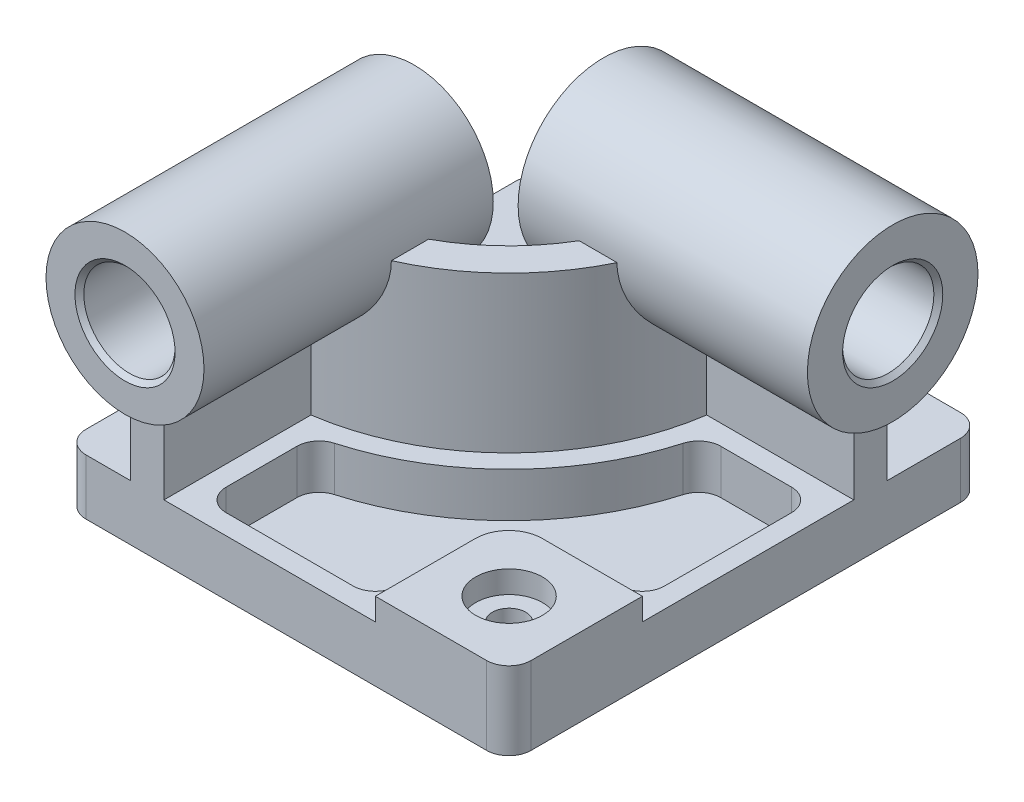
SolidWorks part; units mm, degrees
material "Acier allié"
ref_plane "Plan de face" through (0, 0, 0) normal (0, 0, 1) x (1, 0, 0)
ref_plane "Plan de dessus" through (0, 0, 0) normal (0, 1, 0) x (1, 0, 0)
ref_plane "Plan de droite" through (0, 0, 0) normal (1, 0, 0) x (0, 0, -1)
sketch "Esquisse1" plane through (0, 0, 0) normal (0, 1, 0) x (1, 0, 0)
  line L1 (-100, 106.5) -> (100, 106.5)
  line L2 (-100, 106.5) -> (-100, -106.5)
  line L3 (-100, -106.5) -> (100, -106.5)
  line L4 (100, 106.5) -> (100, -106.5)
  line L5 (-100, 106.5) -> (100, -106.5) construction
  line L6 (-100, -106.5) -> (100, 106.5) construction
  point P0 (0, 0)
  dimension "D1" = 213
  dimension "D2" = 200
extrude "Boss.-Extru.1" add sketch "Esquisse1" along normal blind 25
sketch "Esquisse2" plane through (0, 25, 0) normal (0, 1, 0) x (1, 0, 0)
  line L1 (40, -46.5) -> (100, -46.5)
  line L2 (40, -46.5) -> (40, -106.5)
  line L3 (40, -106.5) -> (100, -106.5)
  line L4 (100, -46.5) -> (100, -106.5)
  line L5 (40, -46.5) -> (100, -106.5) construction
  line L6 (40, -106.5) -> (100, -46.5) construction
  point P0 (70, -76.5)
  point P5 (0, 0)
  dimension "D1" = 60
  dimension "D2" = 60
extrude "Boss.-Extru.2" add sketch "Esquisse2" along normal blind 10
fillet "Congé1" radius 10 4 edges at (-100, 12.5, 106.5) (-100, 12.5, -106.5) (100, 12.5, -106.5) (100, 17.5, 106.5)
fillet "Congé2" radius 15 1 edges at (40, 30, 46.5)
sketch "Esquisse3" plane through (0, 35, 0) normal (0, 1, 0) x (1, 0, 0)
  line L0 (100, -106.3926) -> (100, -76.3926) construction
  line L1 (100, -96.5) -> (100, -46.5) construction
  line L2 (100, -76.3926) -> (70, -76.3926) construction
  dimension "D1" = 30
  dimension "D2" = 30
hole_wizard "Chambrage pour vis à tête hexagonale M86" positions "Esquisse8" profile "Esquisse7" counterbore size "M8" standard "Ansi Metric" end condition through all
sketch "Esquisse8" plane through (0, 35, 0) normal (0, 1, 0) x (1, 0, 0)
  point P0 (70, -76.3926)
  point P2 (0, 0)
sketch "Esquisse7" plane through (70, 35, 76.3926) normal (1, 0, 0) x (0, 0, 1)
  line L0 (0, 0) -> (0, 35)
  line L1 (0, 35) -> (7.5, 35)
  line L3 (7.5, 35) -> (7.5, 10)
  line L4 (7.5, 10) -> (15, 10)
  line L5 (15, 10) -> (15, 0)
  line L7 (15, 0) -> (0, 0)
  line L11 (0, -6.35) -> (0, 107.95) construction
  dimension "Diamètre du perçage jusqu'au prochain" = 15
  dimension "Profondeur du perçage jusqu'au prochain" = 35
  dimension "Diamètre du chambrage" = 30
  dimension "Profondeur du chambrage" = 10
sketch "Esquisse9" plane through (0, 25, 0) normal (0, 1, 0) x (1, 0, 0)
  line L0 (-70, -106.5) -> (-70, -26.5)
  line L1 (-90, -106.5) -> (40, -106.5) construction
  line L2 (100, 63.5) -> (20, 63.5)
  line L3 (100, -46.5) -> (100, 96.5) construction
  line L4 (100, 48.5) -> (33.923, 48.5)
  line L5 (-55, -106.5) -> (-55, -40.423)
  line L6 (100, 63.5) -> (100, 48.5)
  line L7 (-55, -106.5) -> (-70, -106.5)
  arc A0 (20, 63.5) -> (-70, -26.5) centre (-70, 63.5) cw
  arc A1 (33.923, 48.5) -> (-55, -40.423) centre (-70, 63.5) cw
  dimension "D1" = 80
  dimension "D2" = 80
  dimension "D3" = 170
  dimension "D4" = 170
  dimension "D5" = 15
extrude "Boss.-Extru.3" add sketch "Esquisse9" along normal blind 70
sketch "Esquisse10" plane through (0, 25, 0) normal (0, 1, 0) x (1, 0, 0)
  line L12 (-46, -47.9451) -> (-46, -97.5)
  line L13 (-46, -97.5) -> (31, -97.5)
  line L14 (31, -97.5) -> (31, -61.5)
  line L15 (55, -37.5) -> (91, -37.5)
  line L16 (91, -37.5) -> (91, 39.5)
  line L17 (91, 39.5) -> (41.4451, 39.5)
  line L18 (-46, -55.7476) -> (-46, -87.5)
  line L19 (-36, -97.5) -> (21, -97.5)
  line L20 (31, -87.5) -> (31, -61.5)
  line L21 (55, -37.5) -> (81, -37.5)
  line L22 (91, -27.5) -> (91, 29.5)
  line L23 (81, 39.5) -> (49.2476, 39.5)
  arc A2 (81, -37.5) -> (91, -27.5) centre (81, -27.5) ccw
  arc A3 (91, 29.5) -> (81, 39.5) centre (81, 29.5) ccw
  arc A4 (-46, -47.9451) -> (41.4451, 39.5) centre (-70, 63.5) ccw
  arc A5 (55, -37.5) -> (31, -61.5) centre (55, -61.5) ccw
  arc A6 (-38.7419, -46.1309) -> (39.6309, 32.2419) centre (-70, 63.5) ccw
  arc A7 (55, -37.5) -> (31, -61.5) centre (55, -61.5) ccw
  arc A8 (39.6309, 32.2419) -> (49.2476, 39.5) centre (49.2476, 29.5) cw
  arc A9 (-38.7419, -46.1309) -> (-46, -55.7476) centre (-36, -55.7476) ccw
  arc A10 (-46, -87.5) -> (-36, -97.5) centre (-36, -87.5) ccw
  arc A11 (21, -97.5) -> (31, -87.5) centre (21, -87.5) ccw
  dimension "D2" = 10
  dimension "D1" = 9
extrude "Enlèv. mat.-Extru.1" cut sketch "Esquisse10" against normal blind 20
sketch "Esquisse11" plane through (0, 0, 106.5) normal (0, 0, 1) x (1, 0, 0)
  line L0 (-70, 95) -> (-55, 95) construction
  circle A0 centre (-62.5, 95) radius 35.5
  circle A1 centre (-62.5, 95) radius 20.5
  dimension "D1" = 71
  dimension "D2" = 41
extrude "Boss.-Extru.5" add sketch "Esquisse11" against normal blind 130 from offset 10
sketch "Esquisse12" plane through (0, 0, 116.5) normal (0, 0, 1) x (1, 0, 0)
  line L0 (-70, 95) -> (-55, 95) construction
  circle A0 centre (-62.5, 95) radius 20.5
extrude "Enlèv. mat.-Extru.2" cut sketch "Esquisse12" against normal blind 130
sketch "Esquisse13" plane through (100, 0, 0) normal (1, 0, 0) x (0, 0, -1)
  line L0 (48.5, 95) -> (63.5, 95) construction
  circle A0 centre (56, 95) radius 20.5
  circle A1 centre (56, 95) radius 38.3333
  dimension "D2" = 41
  dimension "D1" = 76.6667
extrude "Boss.-Extru.6" add sketch "Esquisse13" against normal blind 130 from offset 10
sketch "Esquisse14" plane through (110, 0, 0) normal (1, 0, 0) x (0, 0, -1)
  line L0 (48.5, 95) -> (63.5, 95) construction
  circle A0 centre (56, 95) radius 20.5
extrude "Enlèv. mat.-Extru.3" cut sketch "Esquisse14" against normal through all
chamfer "Chanfrein1" distance 2 angle 45 4 edges at (-20, 95, -76.5) (110, 95, -76.5) (-42, 95, -13.5) (-42, 95, 116.5)
equation "\"A\"= 213"
equation "\"B\"= 200"
equation "\"C\"= 170"
equation "\"D\"= 130"
equation "\"E\"= 41"
equation "\"X\"= \"A\" / 3"
equation "\"Y\"= \"B\" / 3 + 10"
equation "\"D1@Esquisse1\"=\"A\""
equation "\"D2@Esquisse1\"=\"B\""
equation "\"D3@Esquisse9\"=\"C\""
equation "\"D4@Esquisse9\"=\"C\""
equation "\"D1@Esquisse11\"=\"X\""
equation "\"D2@Esquisse11\"=\"E\""
equation "\"D1@Boss.-Extru.4\"=\"D\""
equation "\"D1@Boss.-Extru.5\"=\"D\""
equation "\"D1@Esquisse13\"=\"Y\""
equation "\"D2@Esquisse13\"=\"E\""
equation "\"D1@Boss.-Extru.6\"=\"D\""
